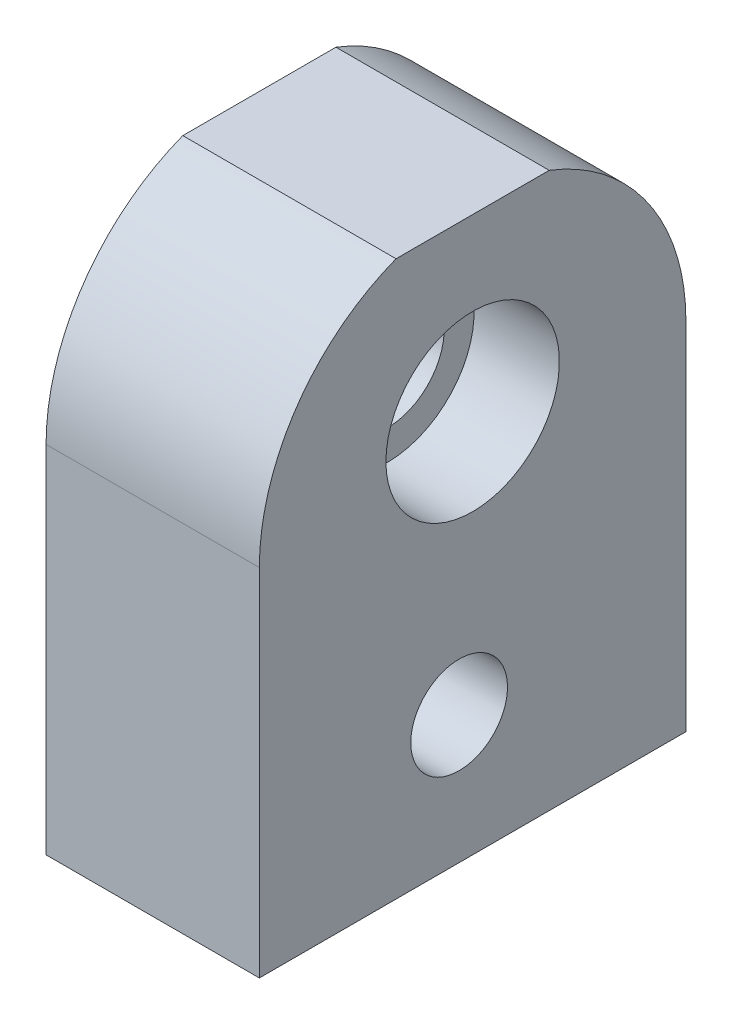
SolidWorks part; units mm, degrees
ref_plane "Front Plane" through (0, 0, 0) normal (0, 0, 1) x (1, 0, 0)
ref_plane "Top Plane" through (0, 0, 0) normal (0, 1, 0) x (1, 0, 0)
ref_plane "Right Plane" through (0, 0, 0) normal (1, 0, 0) x (0, 0, -1)
other "Configuration Table"
sketch "草图1" plane through (0, 0, 0) normal (0, 1, 0) x (1, 0, 0)
  line L0 (0, 0) -> (0, -30)
  line L1 (0, 0) -> (15, 0)
  line L2 (15, 0) -> (15, -30)
  line L3 (15, -30) -> (0, -30)
extrude "凸台-拉伸1" add sketch "草图1" along normal blind 25 contours L3 L0 L1 L2
sketch "草图3" plane through (0, 0, 0) normal (-1, 0, 0) x (0, 0, 1)
  line L0 (15, 25) -> (15, 0) construction
  line L1 (0, 25) -> (30, 25) construction
  line L2 (0, 0) -> (30, 0) construction
  line L7 (0, 25) -> (30, 25)
  circle A2 centre (15, 25) radius 15
  line M7 (30, 25) -> (0, 25)
  dimension "D1" = 0
extrude "凸台-拉伸3" add sketch "草图3" against normal blind 15 contours A2 L7 M7
sketch "草图4" plane through (0, 0, 0) normal (0, -1, 0) x (1, 0, 0)
  line L0 (7.5, 30) -> (7.5, 0) construction
  line L1 (15, 30) -> (0, 30) construction
  line L2 (0, 0) -> (15, 0) construction
  circle A1 centre (7.5, 24) radius 1.65
  circle A2 centre (7.5, 6) radius 1.65
  dimension "D1" = 6
  dimension "D2" = 6
extrude "切除-拉伸2" cut sketch "草图4" against normal blind 10 contours L0 A1 | A1 L0 | L0 A2 | A2 L0
sketch "草图5" plane through (0, 0, 0) normal (-1, 0, 0) x (0, 0, 1)
  line L0 (0, 0) -> (30, 0) construction
  line L4 (0, 25) -> (0, 0) construction
  circle A0 centre (15.95, 9) radius 3.4
  dimension "D2" = 6.8
  dimension "D1" = 9
  dimension "D3" = 15.95
sketch "草图9" plane through (0, 0, 0) normal (-1, 0, 0) x (0, 0, 1)
  line L0 (15, 27) -> (15, 40) construction
  circle A0 centre (15, 27) radius 6.1
  arc A1 (30, 25) -> (0, 25) centre (15, 25) ccw construction
  dimension "D1" = 12.2
extrude "切除-拉伸3" cut sketch "草图9" against normal blind 6
sketch "草图10" plane through (6, 0, 0) normal (-1, 0, 0) x (0, 0, 1)
  circle A0 centre (15, 27) radius 4
  dimension "D1" = 8
extrude "切除-拉伸4" cut sketch "草图10" against normal through all contours A0
mirror "镜向1" about plane through (0, 0, 0) normal (1, 0, 0) of bodies 109 110
delete or keep bodies "实体-删除/保留 1" type delete bodies bodies 109
sketch "草图12" plane through (0, 0, 0) normal (1, 0, 0) x (0, 0, -1)
  line L0 (-15, 25) -> (-15, 39) construction
  line L1 (-20.3852, 39) -> (-9.6148, 39)
  arc A0 (0, 25) -> (-30, 25) centre (-15, 25) ccw construction
  point P9 (-15, 39)
  arc M7 (0, 25) -> (-30, 25) centre (-15, 25) ccw
extrude "切除-拉伸6" cut sketch "草图12" against normal through all and the other way through all contours L1 M7
extrude "切除-拉伸8" cut sketch "草图5" along normal through all
